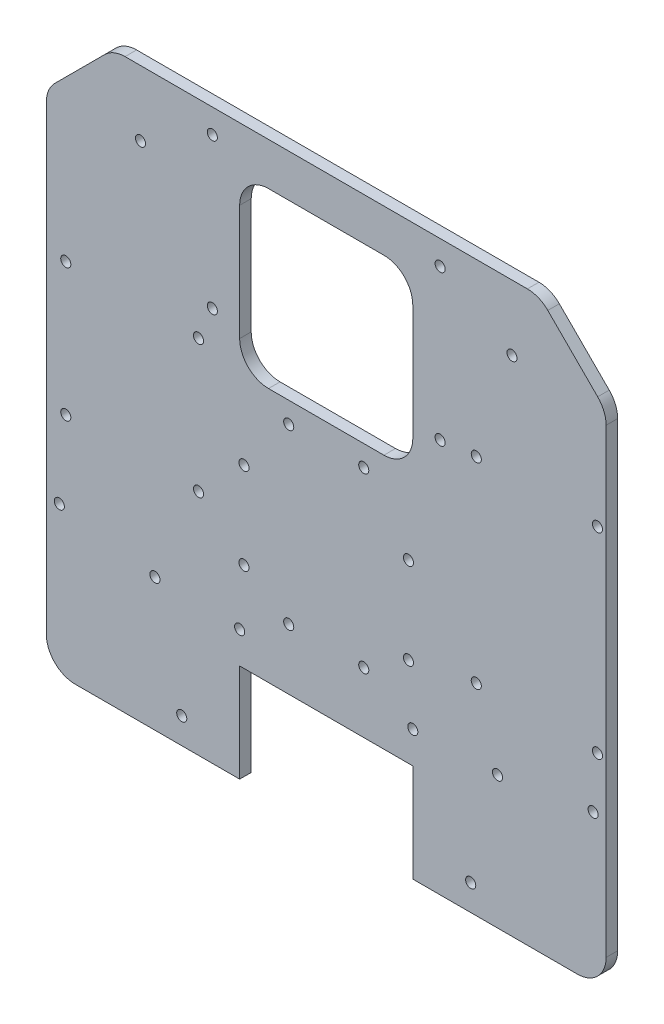
SolidWorks part; units mm, degrees
material "PMMA"
ref_plane "前视基准面" through (0, 0, 0) normal (0, 0, 1) x (1, 0, 0)
ref_plane "上视基准面" through (0, 0, 0) normal (0, 1, 0) x (1, 0, 0)
ref_plane "右视基准面" through (0, 0, 0) normal (1, 0, 0) x (0, 0, -1)
sketch "草图3" plane through (0, 0, 0) normal (0, 0, 1) x (1, 0, 0)
  line L1 (73.5057, 259.0895) -> (196.9372, 259.0895)
  line L2 (25.2215, 210.8052) -> (25.2215, 54.0895)
  line L3 (45.2215, 34.0895) -> (225.2215, 34.0895)
  line L4 (245.2215, 210.8052) -> (245.2215, 54.0895)
  line L6 (31.0793, 224.9474) -> (59.3636, 253.2316)
  line L9 (211.0793, 253.2316) -> (239.3636, 224.9474)
  arc A0 (73.5057, 259.0895) -> (59.3636, 253.2316) centre (73.5057, 239.0895) ccw
  arc A1 (211.0793, 253.2316) -> (196.9372, 259.0895) centre (196.9372, 239.0895) ccw
  arc A2 (31.0793, 224.9474) -> (25.2215, 210.8052) centre (45.2215, 210.8052) ccw
  arc A3 (25.2215, 54.0895) -> (45.2215, 34.0895) centre (45.2215, 54.0895) ccw
  arc A4 (225.2215, 34.0895) -> (245.2215, 54.0895) centre (225.2215, 54.0895) ccw
  arc A5 (245.2215, 210.8052) -> (239.3636, 224.9474) centre (225.2215, 210.8052) ccw
  dimension "D1" = 20
  dimension "D2" = 20
  dimension "D3" = 20
extrude "凸台-拉伸1" add sketch "草图3" along normal blind 4
ref_plane "基准面1" through (0, 0, 4) normal (0, 0, 1) x (1, 0, 0)
sketch "草图4" plane through (0, 0, 4) normal (0, 0, 1) x (1, 0, 0)
  line L0 (135.2215, 259.0895) -> (135.2215, 34.0895) construction
  line L1 (135.2215, 232.7454) -> (174.6915, 232.7454) construction
  line L2 (154.9565, 232.7454) -> (154.9565, 180.6354) construction
  line L4 (135.2215, 180.6354) -> (154.9565, 180.6354) construction
  line L6 (154.9565, 206.6904) -> (187.4334, 206.6904) construction
  line L10 (196.9372, 259.0895) -> (73.5057, 259.0895) construction
  line L11 (45.2215, 34.0895) -> (225.2215, 34.0895) construction
  line L13 (135.2215, 89.0683) -> (165.2215, 89.0683) construction
  circle A5 centre (174.6915, 232.7454) radius 1.75
  circle A14 centre (174.6915, 180.6354) radius 1.75
  circle A15 centre (95.7515, 180.6354) radius 1.75
  circle A16 centre (95.7515, 232.7454) radius 1.75
  circle A17 centre (165.2215, 89.0683) radius 1.75
  circle A18 centre (105.2215, 89.0683) radius 1.75
sketch "草图6" plane through (0, 0, 4) normal (0, 0, 1) x (1, 0, 0)
  line L0 (135.2215, 265.6507) -> (135.2215, 27.2875) construction
  line L1 (187.2215, 181.8801) -> (229.2215, 181.8801) construction
  line L3 (187.2215, 113.8801) -> (229.2215, 113.8801) construction
  line L5 (187.2215, 181.8801) -> (187.2215, 113.8801) construction
  circle A0 centre (187.2215, 181.8801) radius 1.75
  circle A1 centre (229.2215, 181.8801) radius 1.75
  circle A2 centre (229.2215, 113.8801) radius 1.75
  circle A3 centre (187.2215, 113.8801) radius 1.75
extrude "切除-拉伸3" cut sketch "草图6" against normal blind 4
extrude "切除-拉伸4" cut sketch "草图4" against normal blind 4
sketch "草图7" plane through (0, 0, 4) normal (0, 0, 1) x (1, 0, 0)
  circle A0 centre (122.2215, 159.0895) radius 1.75
  circle A1 centre (148.2215, 159.0895) radius 1.75
  circle A2 centre (122.2215, 99.0895) radius 1.75
  circle A3 centre (148.2215, 99.0895) radius 1.75
extrude "切除-拉伸5" cut sketch "草图7" against normal blind 4
sketch "草图8" plane through (0, 0, 4) normal (0, 0, 1) x (1, 0, 0)
  line L0 (25.2215, 132.4474) -> (245.2215, 132.4474) construction
  line L1 (105.2215, 89.0683) -> (165.2215, 89.0683) construction
  line L2 (227.7201, 95.4947) -> (185.2937, 53.0683) construction
  line L4 (25.2215, 210.8052) -> (25.2215, 54.0895) construction
  line L5 (245.2215, 210.8052) -> (245.2215, 54.0895) construction
  line L7 (135.2215, 259.0895) -> (135.2215, 34.0895) construction
  circle A2 centre (227.7201, 95.4947) radius 1.75
  circle A3 centre (185.2937, 53.0683) radius 1.75
  circle A4 centre (42.7229, 95.4947) radius 1.75
  circle A5 centre (85.1493, 53.0683) radius 1.75
extrude "切除-拉伸6" cut sketch "草图8" against normal blind 4
sketch "草图9" plane through (0, 0, 4) normal (0, 0, 1) x (1, 0, 0)
  line L0 (115.2215, 166.3247) -> (155.2215, 166.3247)
  line L2 (135.2215, 226.3247) -> (115.2215, 226.3247)
  line L6 (155.2215, 226.3247) -> (135.2215, 226.3247)
  line L9 (105.2215, 196.1043) -> (105.2215, 176.3247)
  line L10 (105.2215, 166.3247) -> (115.2215, 166.3247)
  line L11 (115.2215, 226.3247) -> (105.2215, 226.3247)
  line L12 (105.2215, 216.3247) -> (105.2215, 196.1043)
  line L13 (155.2215, 226.3247) -> (165.2215, 226.3247)
  line L14 (165.2215, 216.3247) -> (165.2215, 176.3247)
  line L15 (165.2215, 166.3247) -> (155.2215, 166.3247)
  arc A0 (165.2215, 216.3247) -> (155.2215, 226.3247) centre (155.2215, 216.3247) ccw
  arc A1 (165.2215, 176.3247) -> (155.2215, 166.3247) centre (155.2215, 176.3247) cw
  arc A2 (115.2215, 166.3247) -> (105.2215, 176.3247) centre (115.2215, 176.3247) cw
  arc A3 (105.2215, 216.3247) -> (115.2215, 226.3247) centre (115.2215, 216.3247) cw
  dimension "D1" = 10
extrude "切除-拉伸7" cut sketch "草图9" against normal blind 4
sketch "草图10" plane through (0, 0, 4) normal (0, 0, 1) x (1, 0, 0)
  line L0 (135.2215, 259.0895) -> (135.2215, 34.0895) construction
  line L1 (196.9372, 259.0895) -> (73.5057, 259.0895) construction
  line L2 (45.2215, 34.0895) -> (225.2215, 34.0895) construction
  line L3 (106.7215, 109.0895) -> (106.7215, 139.0895) construction
  line L4 (106.7215, 139.0895) -> (163.7215, 139.0895) construction
  line L5 (163.7215, 139.0895) -> (163.7215, 109.0895) construction
  line L6 (163.7215, 109.0895) -> (106.7215, 109.0895) construction
  line L7 (45.2215, 34.0895) -> (225.2215, 34.0895) construction
  circle A2 centre (106.7215, 109.0895) radius 1.75
  circle A3 centre (163.7215, 109.0895) radius 1.75
  circle A4 centre (106.7215, 139.0895) radius 1.75
  circle A5 centre (163.7215, 139.0895) radius 1.75
  dimension "D1" = 75
extrude "切除-拉伸9" cut sketch "草图10" against normal blind 4
sketch "草图11" plane through (0, 0, 4) normal (0, 0, 1) x (1, 0, 0)
  line L0 (26.7439, 218.4589) -> (243.6991, 218.4589) construction
  line L1 (65.8521, 257.5671) -> (65.8521, 34.0895) construction
  line L2 (45.2215, 34.0895) -> (225.2215, 34.0895) construction
  line L3 (204.5909, 131.2717) -> (65.8521, 131.2717) construction
  line L4 (25.2215, 54.0895) -> (245.2215, 54.0895) construction
  line L5 (135.2215, 259.0895) -> (135.2215, 34.0895) construction
  line L10 (73.254, 90.0846) -> (74.553, 87.8346)
  line L11 (73.4502, 218.4589) -> (72.1511, 220.7089)
  line L12 (196.9372, 259.0895) -> (73.5057, 259.0895) construction
  line L13 (204.5909, 218.4589) -> (204.5909, 44.0846) construction
  line L26 (75.8521, 90.0846) -> (75.8521, 218.4589) construction
  line L27 (72.1511, 220.7089) -> (69.553, 220.7089)
  line L28 (69.553, 220.7089) -> (68.254, 218.4589)
  line L29 (68.254, 218.4589) -> (69.553, 216.2089)
  line L30 (69.553, 216.2089) -> (72.1511, 216.2089)
  line L31 (72.1511, 216.2089) -> (73.4502, 218.4589)
  line L32 (77.1511, 87.8346) -> (78.4502, 90.0846)
  line L33 (74.553, 87.8346) -> (77.1511, 87.8346)
  line L34 (78.4502, 90.0846) -> (77.1511, 92.3346)
  line L35 (74.553, 92.3346) -> (73.254, 90.0846)
  line L36 (77.1511, 92.3346) -> (74.553, 92.3346)
  line L37 (191.9928, 90.0846) -> (193.2918, 87.8346)
  line L38 (195.8899, 87.8346) -> (197.1889, 90.0846)
  line L39 (193.2918, 87.8346) -> (195.8899, 87.8346)
  line L40 (197.1889, 90.0846) -> (195.8899, 92.3346)
  line L41 (193.2918, 92.3346) -> (191.9928, 90.0846)
  line L42 (195.8899, 92.3346) -> (193.2918, 92.3346)
  line L43 (196.9928, 218.4589) -> (198.2918, 216.2089)
  line L44 (200.8899, 216.2089) -> (202.1889, 218.4589)
  line L45 (198.2918, 216.2089) -> (200.8899, 216.2089)
  line L46 (202.1889, 218.4589) -> (200.8899, 220.7089)
  line L47 (198.2918, 220.7089) -> (196.9928, 218.4589)
  line L48 (200.8899, 220.7089) -> (198.2918, 220.7089)
  arc A0 (31.0793, 224.9474) -> (25.2215, 210.8052) centre (45.2215, 210.8052) ccw construction
  arc A1 (245.2215, 210.8052) -> (239.3636, 224.9474) centre (225.2215, 210.8052) ccw construction
  arc A2 (73.5057, 259.0895) -> (59.3636, 253.2316) centre (73.5057, 239.0895) ccw construction
  circle A3 centre (70.8521, 218.4589) radius 1.75
  circle A12 centre (75.8521, 90.0846) radius 1.75
  circle A13 centre (194.5909, 90.0846) radius 1.75
  circle A15 centre (199.5909, 218.4589) radius 1.75
  circle A16 centre (70.8521, 218.4589) radius 2.25 construction
  point P26 (65.8521, 218.4589)
  dimension "D1" = 4.5
extrude "切除-拉伸10" cut sketch "草图11" against normal up to next
ref_plane "基准面2" through (0, 0, 4) normal (0, 0, 1) x (1, 0, 0)
sketch "草图12" plane through (0, 0, 4) normal (0, 0, 1) x (1, 0, 0)
  line L0 (41.9614, 172.3122) -> (41.9614, 165.6511) construction
  line L1 (41.9614, 172.3122) -> (93.9614, 172.3122)
  line L2 (41.9614, 172.3122) -> (41.9614, 120.3122)
  line L3 (41.9614, 120.3122) -> (93.9614, 120.3122)
  line L4 (93.9614, 172.3122) -> (93.9614, 120.3122)
  line L5 (41.9614, 172.3122) -> (93.9614, 120.3122) construction
  line L6 (41.9614, 120.3122) -> (93.9614, 172.3122) construction
  line L7 (41.9614, 172.3122) -> (41.9614, 166.5784) construction
  line L8 (41.9614, 166.5784) -> (41.9614, 164.5784) construction
  line L9 (93.9614, 172.3122) -> (93.9614, 169.3122) construction
  line L10 (93.9614, 169.3122) -> (90.9614, 169.3122) construction
  circle A0 centre (90.9614, 169.3122) radius 1.75
  circle A1 centre (90.9614, 123.3122) radius 1.75
  circle A2 centre (44.9614, 123.3122) radius 1.75
  circle A3 centre (44.9614, 169.3122) radius 1.75
  point P0 (67.9614, 146.3122)
  point P20 (67.9614, 146.3122)
  dimension "D1" = 4
extrude "切除-拉伸13" cut sketch "草图12" against normal through all contours A3 | A2 | A1 | A0
sketch "草图13" plane through (0, 0, 4) normal (0, 0, 1) x (1, 0, 0)
  line L0 (45.2215, 34.0895) -> (225.2215, 34.0895) construction
  line L1 (105.2215, 68.0683) -> (165.2215, 68.0683)
  line L2 (105.2215, 68.0683) -> (105.2215, 34.0895)
  line L3 (105.2215, 34.0895) -> (165.2215, 34.0895)
  line L4 (165.2215, 68.0683) -> (165.2215, 34.0895)
  line L5 (165.2215, 54.0895) -> (105.2215, 54.0895)
  line L6 (25.2215, 54.0895) -> (245.2215, 54.0895) construction
extrude "切除-拉伸14" cut sketch "草图13" against normal blind 10 contours L4 L5 L2 L3
sketch "草图14" plane through (0, 0, 0) normal (0, 0, 1) x (1, 0, 0)
  line L0 (105.2215, 68.0683) -> (165.2215, 68.0683)
  line L10 (105.2215, 68.0683) -> (165.2215, 68.0683)
  line L11 (165.2215, 68.0683) -> (165.2215, 34.0895)
  line L12 (165.2215, 34.0895) -> (225.2215, 34.0895)
  line L13 (245.2215, 54.0895) -> (245.2215, 210.8052)
  line L14 (239.3636, 224.9474) -> (211.0793, 253.2316)
  line L15 (196.9372, 259.0895) -> (73.5057, 259.0895)
  line L16 (59.3636, 253.2316) -> (31.0793, 224.9474)
  line L17 (25.2215, 210.8052) -> (25.2215, 54.0895)
  line L18 (45.2215, 34.0895) -> (105.2215, 34.0895)
  line L19 (105.2215, 34.0895) -> (105.2215, 68.0683)
  line L21 (165.2215, 44.0895) -> (165.2215, 34.0895)
  line L22 (165.2215, 34.0895) -> (225.2215, 34.0895)
  line L23 (245.2215, 54.0895) -> (245.2215, 210.8052)
  line L24 (239.3636, 224.9474) -> (211.0793, 253.2316)
  line L25 (196.9372, 259.0895) -> (73.5057, 259.0895)
  line L26 (59.3636, 253.2316) -> (31.0793, 224.9474)
  line L27 (25.2215, 210.8052) -> (25.2215, 54.0895)
  line L28 (45.2215, 34.0895) -> (105.2215, 34.0895)
  line L29 (105.2215, 34.0895) -> (105.2215, 44.0895)
  line L30 (38.2215, 210.8052) -> (38.2215, 54.0895)
  line L31 (232.2215, 54.0895) -> (232.2215, 213.8052)
  line L32 (196.9372, 241.0895) -> (73.5057, 241.0895)
  line L33 (73.5057, 241.0895) -> (65.5057, 241.0895)
  line L34 (38.2215, 210.8052) -> (38.2215, 213.8052)
  line L35 (196.9372, 241.0895) -> (204.9372, 241.0895)
  line L36 (232.2215, 210.8052) -> (232.2215, 213.8052)
  line L40 (95.2215, 78.0683) -> (175.2215, 78.0683)
  line L41 (175.2215, 78.0683) -> (175.2215, 44.0895)
  line L42 (175.2215, 44.0895) -> (225.2215, 44.0895)
  line L43 (235.2215, 54.0895) -> (235.2215, 210.8052)
  line L44 (232.2925, 217.8763) -> (204.0083, 246.1606)
  line L45 (196.9372, 249.0895) -> (73.5057, 249.0895)
  line L46 (66.4347, 246.1606) -> (38.1504, 217.8763)
  line L47 (35.2215, 210.8052) -> (35.2215, 54.0895)
  line L48 (45.2215, 44.0895) -> (95.2215, 44.0895)
  line L49 (95.2215, 44.0895) -> (95.2215, 78.0683)
  line L50 (105.2215, 78.0683) -> (165.2215, 78.0683)
  line L52 (175.2215, 44.0895) -> (222.2215, 44.0895)
  line L54 (229.2925, 220.8763) -> (212.0083, 238.1606)
  line L56 (58.4347, 238.1606) -> (41.1504, 220.8763)
  line L58 (48.2215, 44.0895) -> (95.2215, 44.0895)
  line L61 (105.2215, 78.0683) -> (105.2215, 68.0683)
  line L62 (95.2215, 44.0895) -> (105.2215, 44.0895)
  line L63 (165.2215, 78.0683) -> (165.2215, 68.0683)
  line L64 (175.2215, 44.0895) -> (165.2215, 44.0895)
  arc A6 (225.2215, 34.0895) -> (245.2215, 54.0895) centre (225.2215, 54.0895) ccw
  arc A7 (245.2215, 210.8052) -> (239.3636, 224.9474) centre (225.2215, 210.8052) ccw
  arc A8 (211.0793, 253.2316) -> (196.9372, 259.0895) centre (196.9372, 239.0895) ccw
  arc A9 (73.5057, 259.0895) -> (59.3636, 253.2316) centre (73.5057, 239.0895) ccw
  arc A10 (31.0793, 224.9474) -> (25.2215, 210.8052) centre (45.2215, 210.8052) ccw
  arc A11 (25.2215, 54.0895) -> (45.2215, 34.0895) centre (45.2215, 54.0895) ccw
  arc A12 (225.2215, 34.0895) -> (245.2215, 54.0895) centre (225.2215, 54.0895) ccw
  arc A13 (245.2215, 210.8052) -> (239.3636, 224.9474) centre (225.2215, 210.8052) ccw
  arc A14 (211.0793, 253.2316) -> (196.9372, 259.0895) centre (196.9372, 239.0895) ccw
  arc A15 (73.5057, 259.0895) -> (59.3636, 253.2316) centre (73.5057, 239.0895) ccw
  arc A16 (31.0793, 224.9474) -> (25.2215, 210.8052) centre (45.2215, 210.8052) ccw
  arc A17 (25.2215, 54.0895) -> (45.2215, 34.0895) centre (45.2215, 54.0895) ccw
  arc A18 (222.2215, 44.0895) -> (232.2215, 54.0895) centre (222.2215, 54.0895) ccw
  arc A19 (48.2215, 44.0895) -> (38.2215, 54.0895) centre (48.2215, 54.0895) cw
  arc A20 (212.0083, 238.1606) -> (204.9372, 241.0895) centre (204.9372, 231.0895) ccw
  arc A21 (58.4347, 238.1606) -> (65.5057, 241.0895) centre (65.5057, 231.0895) cw
  arc A22 (232.2215, 213.8052) -> (229.2925, 220.8763) centre (222.2215, 213.8052) ccw
  arc A23 (38.2215, 213.8052) -> (41.1504, 220.8763) centre (48.2215, 213.8052) cw
  arc A24 (225.2215, 44.0895) -> (235.2215, 54.0895) centre (225.2215, 54.0895) ccw
  arc A25 (235.2215, 210.8052) -> (232.2925, 217.8763) centre (225.2215, 210.8052) ccw
  arc A26 (204.0083, 246.1606) -> (196.9372, 249.0895) centre (196.9372, 239.0895) ccw
  arc A27 (73.5057, 249.0895) -> (66.4347, 246.1606) centre (73.5057, 239.0895) ccw
  arc A28 (38.1504, 217.8763) -> (35.2215, 210.8052) centre (45.2215, 210.8052) ccw
  arc A29 (35.2215, 54.0895) -> (45.2215, 44.0895) centre (45.2215, 54.0895) ccw
  dimension "D3" = 10
  dimension "D4" = 10
  dimension "D1" = 0
  dimension "D2" = 10
extrude "切除-拉伸16" cut sketch "草图14" along normal blind 10 contours L34 A23 L56 A21 L33 L32 L35 A20 L54 A22 L31 A18 L52 L64 L21 L22 A12 L23 A13 L24 A14 L25 A15 L26 A16 L27 A17 L28 L29 L62 L58 A19 L30 | L63 L50 L61 L0
